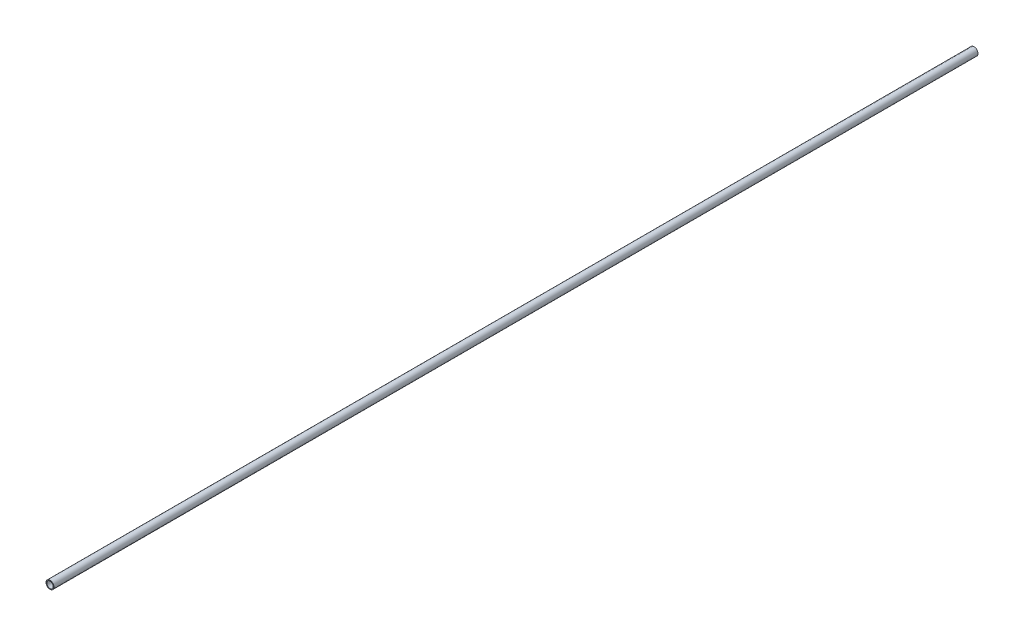
SolidWorks part; units mm, degrees
material "1023 Carbon Steel Sheet (SS)"
ref_plane "Front Plane" through (0, 0, 0) normal (0, 0, 1) x (1, 0, 0)
ref_plane "Top Plane" through (0, 0, 0) normal (0, 1, 0) x (1, 0, 0)
ref_plane "Right Plane" through (0, 0, 0) normal (1, 0, 0) x (0, 0, -1)
sketch "Sketch1" plane through (0, 0, 0) normal (0, 0, 1) x (1, 0, 0)
  circle A0 centre (0, 0) radius 6.35
  circle A1 centre (0, 0) radius 7.874
  dimension "D1" = 12.7
  dimension "D2" = 15.748
extrude "Boss-Extrude1" add sketch "Sketch1" along normal blind 1838.452
